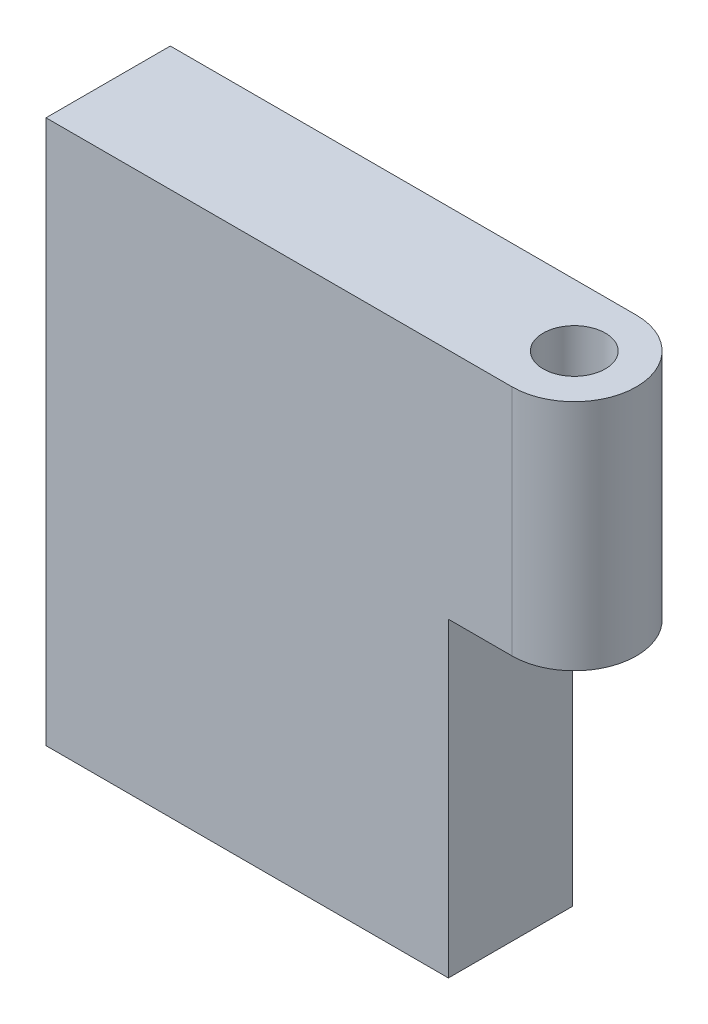
SolidWorks part; units mm, degrees
ref_plane "Front Plane" through (0, 0, 0) normal (0, 0, 1) x (1, 0, 0)
ref_plane "Top Plane" through (0, 0, 0) normal (0, 1, 0) x (1, 0, 0)
ref_plane "Right Plane" through (0, 0, 0) normal (1, 0, 0) x (0, 0, -1)
sketch "Sketch1" plane through (0, 0, 0) normal (0, 1, 0) x (1, 0, 0)
  line L1 (0, -4) -> (-30, -4)
  line L2 (0, -4) -> (0, 4)
  line L3 (0, 4) -> (-30, 4)
  line L4 (-30, -4) -> (-30, 4)
  circle A0 centre (0, 0) radius 4
  point P7 (0, 0)
  point P8 (0, 0)
  dimension "D1" = 30
  dimension "D3" = 8
  dimension "D2" = 8
extrude "Boss-Extrude1" add sketch "Sketch1" along normal blind 15 contours A0 L3 L4 L1 | L2 A0 | L2 A0
sketch "Sketch2" plane through (0, 15, 0) normal (0, 1, 0) x (1, 0, 0)
  circle A0 centre (0, 0) radius 2
extrude "Cut-Extrude1" cut sketch "Sketch2" against normal through all
sketch "Sketch3" plane through (0, 0, 0) normal (0, -1, 0) x (1, 0, 0)
  line L0 (0, -4) -> (-30, -4) construction
  line L1 (-30, 4) -> (-4.1, 4)
  line L2 (-30, 4) -> (-30, -4)
  line L3 (-30, -4) -> (-4.1, -4)
  line L4 (-4.1, 4) -> (-4.1, -4)
  circle A0 centre (0, 0) radius 2 construction
  point P9 (-4.1, 0)
  dimension "D1" = 4.1
extrude "Boss-Extrude2" add sketch "Sketch3" along normal blind 20
